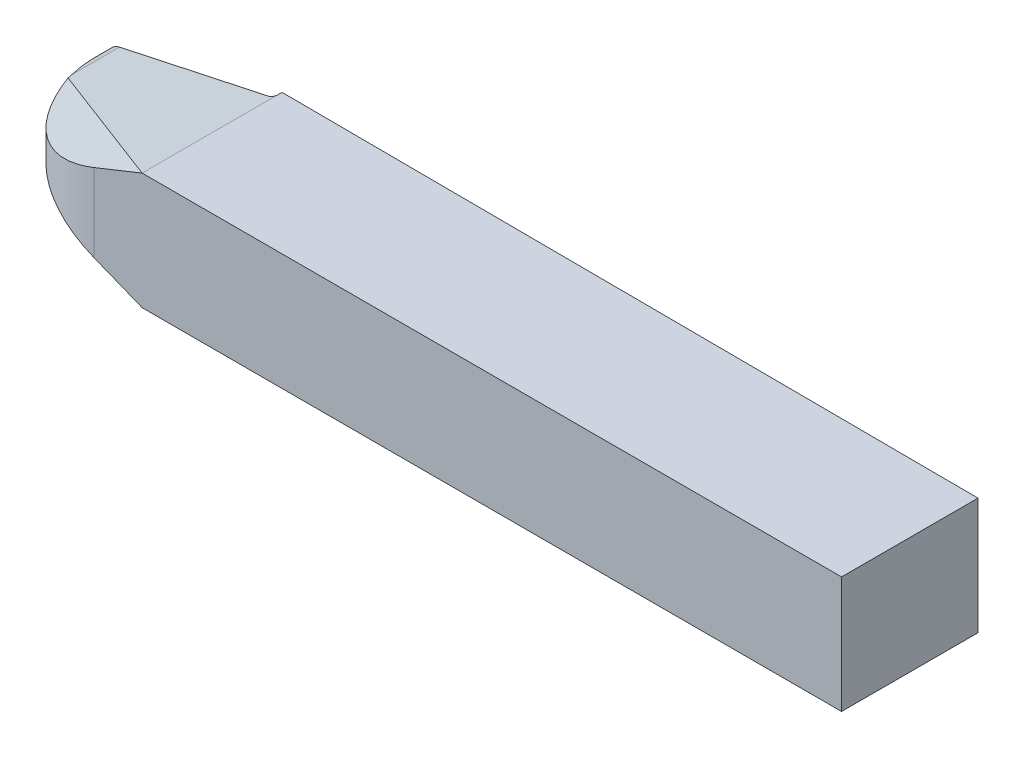
SolidWorks part; units mm, degrees
ref_plane "Спереди" through (0, 0, 0) normal (0, 0, 1) x (1, 0, 0)
ref_plane "Сверху" through (0, 0, 0) normal (0, 1, 0) x (1, 0, 0)
ref_plane "Справа" through (0, 0, 0) normal (1, 0, 0) x (0, 0, -1)
sketch "Эскиз1" plane through (0, 0, 0) normal (0, 0, 1) x (1, 0, 0)
  line L0 (0, 10) -> (-27, 10) construction
  line L1 (0, 0) -> (120, 0)
  line L2 (0, 0) -> (0, 20) construction
  line L4 (120, 0) -> (120, 20)
  line L5 (0, 20) -> (-27.7431, 12.9065)
  line L6 (0, 0) -> (-27.7431, 7.0935)
  line L7 (0, 20) -> (120, 20)
  arc A0 (-27.7431, 12.9065) -> (-27.7431, 7.0935) centre (-27, 10) ccw
  point P8 (-30, 10)
  dimension "D2" = 3
  dimension "D1" = 20
  dimension "D3" = 150
  dimension "D4" = 30
extrude "Бобышка-Вытянуть1" add sketch "Эскиз1" along normal blind 24
sketch "Эскиз2" plane through (0, 0, 0) normal (0, 1, 0) x (1, 0, 0)
  line L0 (-30, 0) -> (-27.5412, -9.1764)
  line L2 (-27.7431, 0) -> (-30, 0) construction
  line L3 (-27.7431, 0) -> (-27.7431, -24) construction
  line L5 (0, 0) -> (-27.7431, 0) construction
  line L6 (-27.7431, -24) -> (0, -24) construction
  line L8 (-27.7431, 0) -> (-30, 0) construction
  line L9 (-27.7431, 0) -> (-27.7431, -24) construction
  line L10 (-30, 0) -> (-0.8056, -1.53)
  line L11 (0, 0) -> (-27.7431, 0) construction
  line L12 (-8.2227, -24) -> (0, -24)
  line L14 (-30, 0) -> (-30, -24) construction
  line L15 (0, 0) -> (155.0356, -0.7655)
  line L16 (155.0356, -0.7655) -> (155.0356, -24)
  line L17 (155.0356, -24) -> (0, -24)
  line L18 (0, 0) -> (0, -0.7655)
  arc A0 (-27.5412, -9.1764) -> (-8.2227, -24) centre (-8.2227, -4) ccw
  arc A1 (-0.8056, -1.53) -> (0, -0.7655) centre (-0.7655, -0.7655) ccw
  dimension "D2" = 20
  dimension "D1" = 15
  dimension "D3" = 3
extrude "Вырез-Вытянуть1" cut sketch "Эскиз2" along normal blind 24 flip side to cut
sketch "Эскиз3" plane through (0, 0, 0) normal (1, 0, 0) x (0, 0, -1)
  line L0 (0, 20) -> (-25.8926, 13.0621)
  line L1 (-25.8926, 13.0621) -> (-25.8926, 20)
  line L2 (-25.8926, 20) -> (0, 20)
  line L3 (-24, 20) -> (1.5934, 26.8577)
  dimension "D1" = 15
  dimension "D2" = 15
ref_plane "Плоскость1" through (-8.5813, 21.4584, 5.7498) normal (-0.3603, 0.901, 0.2414) x (0.9328, 0.3481, 0.0933)
sketch "Эскиз6" plane through (-8.5813, 21.4584, 5.7498) normal (-0.3603, 0.901, 0.2414) x (0.9328, 0.3481, 0.0933)
  line L15 (-26.8378, 10.3607) -> (16.7994, 10.3607)
  line L16 (-26.8378, 10.3607) -> (-26.8378, -24.9399)
  line L17 (-26.8378, -24.9399) -> (16.7994, -24.9399)
  line L18 (16.7994, 10.3607) -> (16.7994, -24.9399)
extrude "Вырез-Вытянуть2" cut sketch "Эскиз6" along normal blind 24
ref_plane "Плоскость2" through (0, 10, 0) normal (0, -1, 0) x (-1, 0, 0)
mirror "Зеркальное отражение1" about plane through (0, 10, 0) normal (0, -1, 0) of "Вырез-Вытянуть2"
